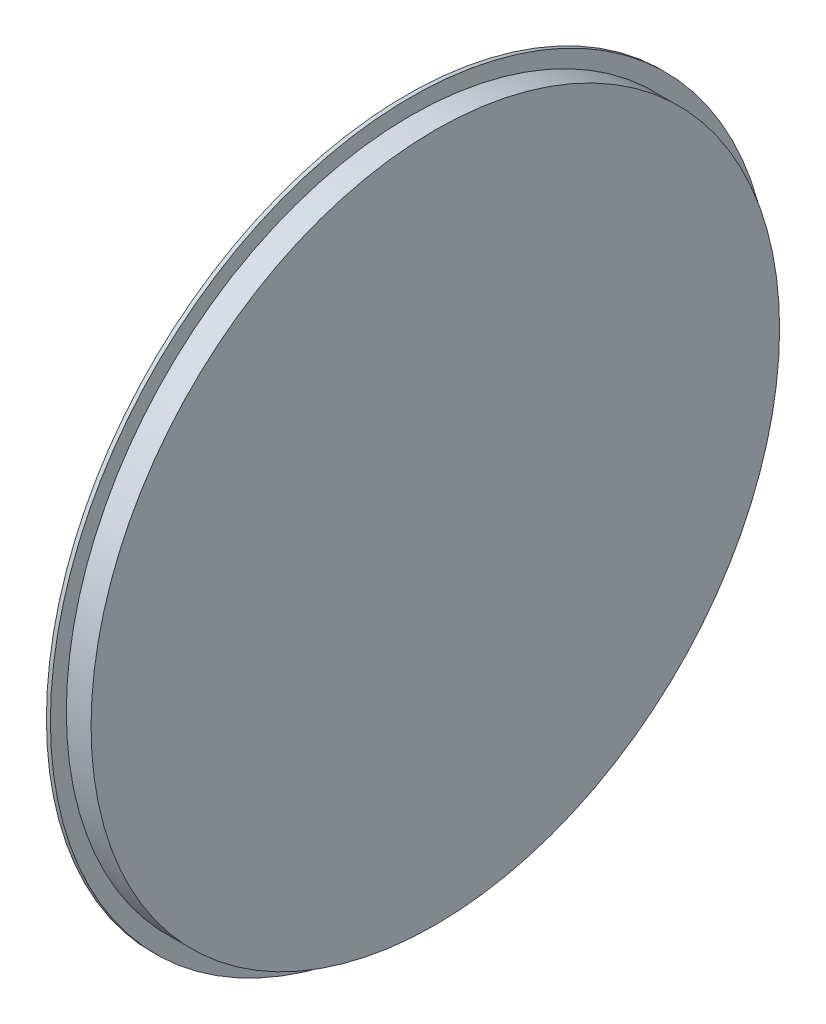
SolidWorks part; units mm, degrees
ref_plane "Front Plane" through (0, 0, 0) normal (0, 0, 1) x (1, 0, 0)
ref_plane "Top Plane" through (0, 0, 0) normal (0, 1, 0) x (1, 0, 0)
ref_plane "Right Plane" through (0, 0, 0) normal (1, 0, 0) x (0, 0, -1)
sketch "Sketch1" plane through (0, 0, 0) normal (0, 0, 1) x (1, 0, 0)
  line L0 (0, 0) -> (0, 274.193)
  line L1 (0, 274.193) -> (-19.685, 274.193)
  line L2 (-19.685, 274.193) -> (-19.685, 286.893)
  line L3 (-19.685, 286.893) -> (-22.86, 286.893)
  line L4 (-22.86, 286.893) -> (-22.86, 0)
  line L5 (-22.86, 0) -> (0, 0)
  line L6 (0, 0) -> (99.2272, 0) construction
  point P3 (-9.8425, 274.193)
  dimension "D1" = 548.386
  dimension "D2" = 12.7
  dimension "D3" = 22.86
  dimension "D4" = 3.175
revolve "Revolve1" add sketch "Sketch1" angle 360 about L6
sketch "Sketch2" plane through (-22.86, 0, 0) normal (-1, 0, 0) x (0, 0, 1)
  text T0 "REMOVE BEFORE\r\n         FLIGHT" font "Century Gothic" height 38.1
extrude "Cut-Extrude1" cut sketch "Sketch2" against normal blind 1.27
